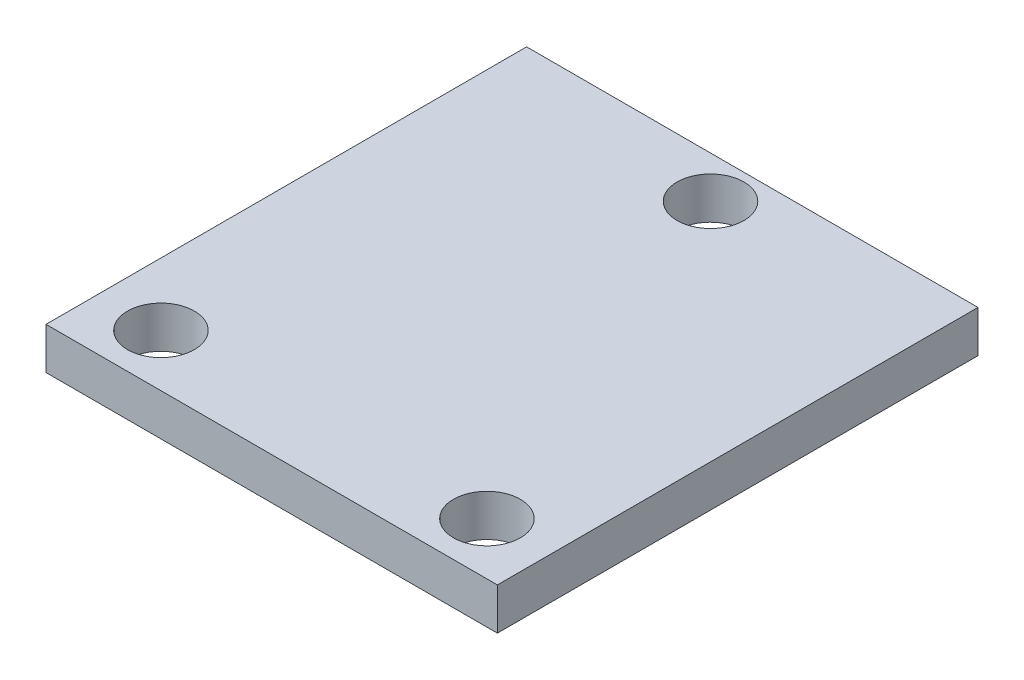
SolidWorks part; units mm, degrees
ref_plane "前视基准面" through (0, 0, 0) normal (0, 0, 1) x (1, 0, 0)
ref_plane "上视基准面" through (0, 0, 0) normal (0, 1, 0) x (1, 0, 0)
ref_plane "右视基准面" through (0, 0, 0) normal (1, 0, 0) x (0, 0, -1)
other "Configuration Table"
sketch "草图1" plane through (0, 0, 0) normal (0, 1, 0) x (1, 0, 0)
  line L1 (0, 0) -> (10.8, 0)
  line L2 (0, 0) -> (0, -11.5)
  line L3 (0, -11.5) -> (10.8, -11.5)
  line L4 (10.8, 0) -> (10.8, -11.5)
  circle A0 centre (5.4, -1) radius 0.8
  circle A1 centre (9.3, -10.25) radius 0.8
  circle A2 centre (1.5, -10.25) radius 0.8
  point P8 (5.4, 0)
  point P12 (0, 0)
  point P13 (5.2778, -2.3653)
  point P14 (7.0787, -2.3586)
  point P15 (0, 0)
  point P16 (0, 0)
  point P17 (1.2756, -9.1106)
  point P18 (0, 0)
  dimension "D3" = 1.6
  dimension "D1" = 10.8
  dimension "D2" = 11.5
  dimension "D4" = 1
  dimension "D5" = 1.25
  dimension "D6" = 1.5
  dimension "D7" = 1.5
extrude "凸台-拉伸1" add sketch "草图1" along normal blind 1
